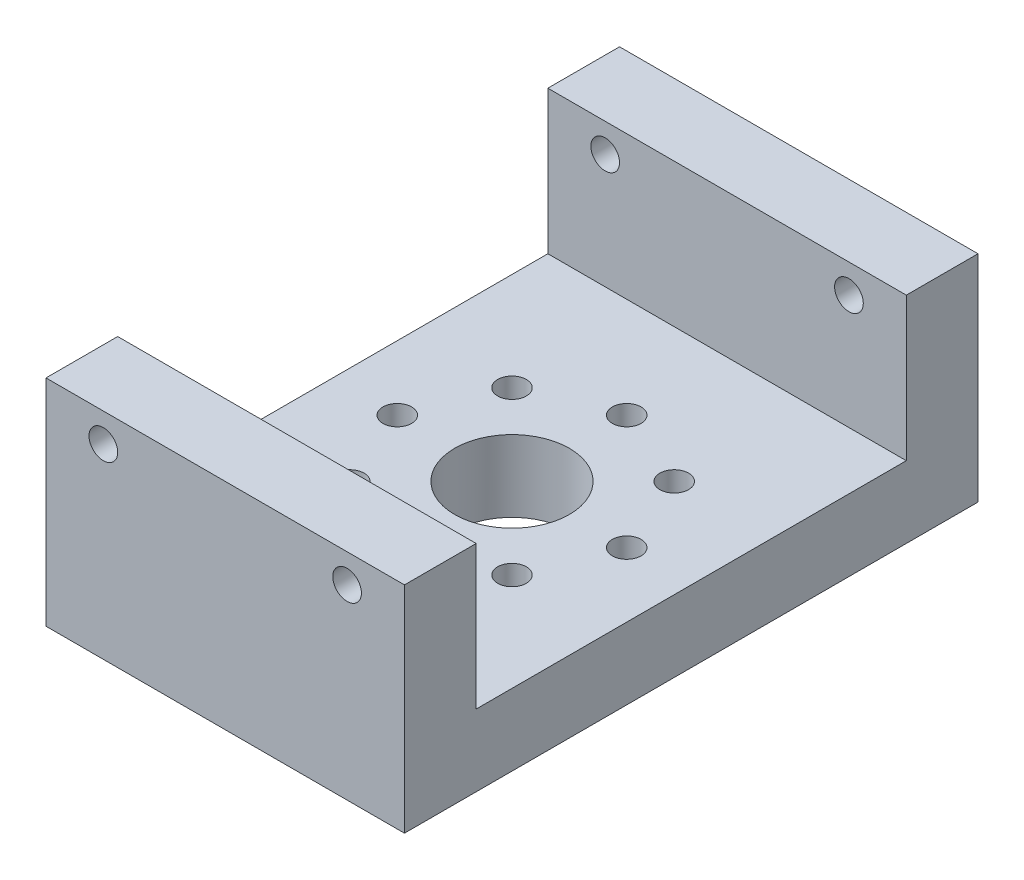
SolidWorks part; units mm, degrees
material "1060 Alloy"
ref_plane "Front Plane" through (0, 0, 0) normal (0, 0, 1) x (1, 0, 0)
ref_plane "Top Plane" through (0, 0, 0) normal (0, 1, 0) x (1, 0, 0)
ref_plane "Right Plane" through (0, 0, 0) normal (1, 0, 0) x (0, 0, -1)
sketch "Sketch1" plane through (0, 0, 0) normal (0, 1, 0) x (1, 0, 0)
  line L1 (-12.5, 20) -> (12.5, 20)
  line L2 (-12.5, 20) -> (-12.5, -20)
  line L3 (-12.5, -20) -> (12.5, -20)
  line L4 (12.5, 20) -> (12.5, -20)
  line L5 (-12.5, 20) -> (12.5, -20) construction
  line L6 (-12.5, -20) -> (12.5, 20) construction
  point P0 (0, 0)
  dimension "D1" = 40
  dimension "D2" = 25
extrude "Boss-Extrude1" add sketch "Sketch1" along normal blind 5
sketch "Sketch2" [suppressed] plane through (0, 5, 0) normal (0, 1, 0) x (1, 0, 0)
  line L0 (-5, 0) -> (5, 0) construction
  circle A0 centre (-5, 0) radius 1
  circle A1 centre (5, 0) radius 1
  point P4 (0, 0)
  dimension "D2" = 2
  dimension "D3" = 2
  dimension "D1" = 10
extrude "Cut-Extrude1" [suppressed] cut sketch "Sketch2" against normal through all
sketch "Sketch3" [suppressed] plane through (0, 5, 0) normal (0, 1, 0) x (1, 0, 0)
  circle A0 centre (-5, 0) radius 2
  circle A1 centre (5, 0) radius 2
  dimension "D1" = 4
  dimension "D2" = 4
extrude "Cut-Extrude2" [suppressed] cut sketch "Sketch3" against normal blind 2
sketch "Sketch5" plane through (0, 5, 0) normal (0, 1, 0) x (1, 0, 0)
  line L0 (12.5, -20) -> (12.5, 20) construction
  line L1 (-12.5, 20) -> (12.5, 20)
  line L2 (-12.5, 20) -> (-12.5, 15)
  line L3 (-12.5, 15) -> (12.5, 15)
  line L4 (12.5, 20) -> (12.5, 15)
  line L5 (0, 15) -> (0, -15) construction
  line L6 (-12.5, -20) -> (12.5, -20)
  line L7 (-12.5, -20) -> (-12.5, -15)
  line L8 (-12.5, -15) -> (12.5, -15)
  line L9 (12.5, -20) -> (12.5, -15)
  point P14 (0, 0)
  dimension "D1" = 30
extrude "Boss-Extrude2" add sketch "Sketch5" along normal blind 10
sketch "Sketch6" plane through (0, 0, 20) normal (0, 0, 1) x (1, 0, 0)
  line L0 (-8.5, 13) -> (8.5, 13) construction
  line L1 (0, 0) -> (0, 15) construction
  line L2 (-12.5, 15) -> (12.5, 15) construction
  circle A0 centre (-8.5, 13) radius 1
  circle A1 centre (8.5, 13) radius 1
  point P10 (0, 13)
  dimension "D1" = 2
  dimension "D2" = 2
  dimension "D3" = 17
  dimension "D4" = 2
extrude "Cut-Extrude3" cut sketch "Sketch6" against normal through all
sketch "Sketch7" plane through (0, 0, 0) normal (0, -1, 0) x (1, 0, 0)
  circle A0 centre (0, 0) radius 4
  circle A1 centre (0, 0) radius 8
  circle A2 centre (0, 8) radius 1
  circle A3 centre (5.6569, 5.6569) radius 1
  circle A4 centre (8, 0) radius 1
  circle A5 centre (5.6569, -5.6569) radius 1
  circle A6 centre (0, -8) radius 1
  circle A7 centre (-5.6569, -5.6569) radius 1
  circle A8 centre (-8, 0) radius 1
  circle A9 centre (-5.6569, 5.6569) radius 1
  point P23 (0, 0)
  dimension "D1" = 8
  dimension "D2" = 16
  dimension "D3" = 2
  dimension "D4" = 8
extrude "Cut-Extrude4" cut sketch "Sketch7" against normal blind 10 contours A1 A2 | A1 A2 | A1 A3 | A1 A3 | A1 A4 | A1 A4 | A1 A5 | A1 A5 | A1 A6 | A1 A6 | A1 A7 | A1 A7 | A1 A8 | A1 A8 | A1 A9 | A1 A9 | A0
